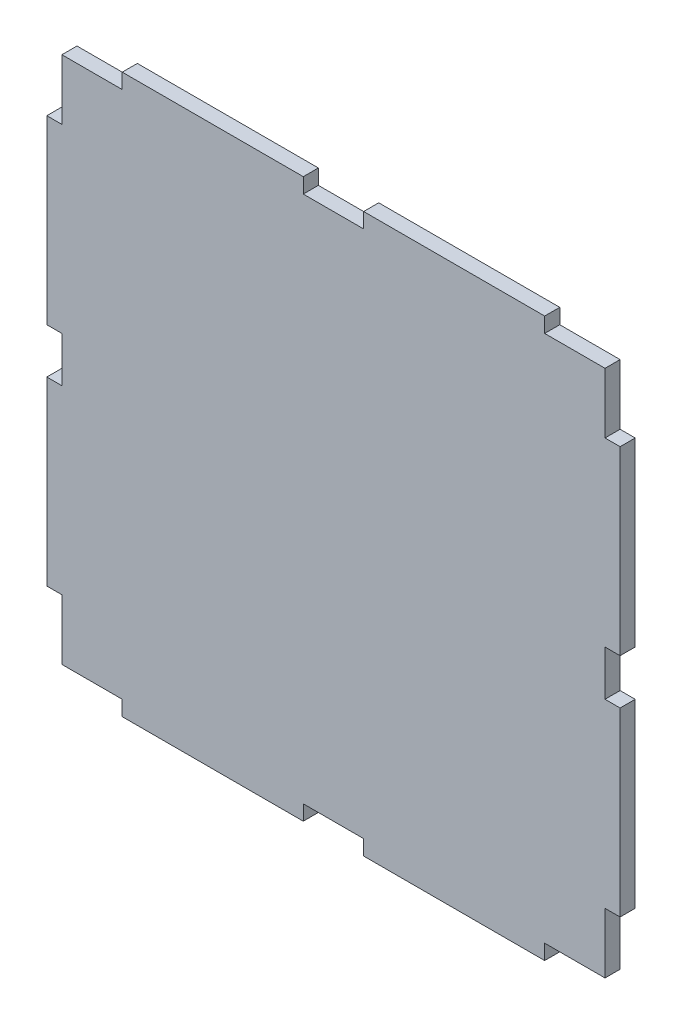
SolidWorks part; units mm, degrees
ref_plane "Front Plane" through (0, 0, 0) normal (0, 0, 1) x (1, 0, 0)
ref_plane "Top Plane" through (0, 0, 0) normal (0, 1, 0) x (1, 0, 0)
ref_plane "Right Plane" through (0, 0, 0) normal (1, 0, 0) x (0, 0, -1)
sketch "Sketch5" plane through (0, 0, 0) normal (0, 0, 1) x (1, 0, 0)
  line L0 (259.6128, -169.2784) -> (259.6128, -391.5284) construction
  line L1 (145.3128, -169.2784) -> (373.9128, -169.2784)
  line L2 (145.3128, -169.2784) -> (145.3128, -391.5284)
  line L3 (145.3128, -391.5284) -> (373.9128, -391.5284)
  line L4 (373.9128, -169.2784) -> (373.9128, -391.5284)
  line L5 (170.7128, -169.2784) -> (246.9128, -169.2784)
  line L6 (170.7128, -169.2784) -> (170.7128, -162.9284)
  line L7 (170.7128, -162.9284) -> (246.9128, -162.9284)
  line L8 (246.9128, -169.2784) -> (246.9128, -162.9284)
  line L9 (138.9628, -194.6784) -> (145.3128, -194.6784)
  line L10 (138.9628, -194.6784) -> (138.9628, -270.8784)
  line L11 (138.9628, -270.8784) -> (145.3128, -270.8784)
  line L12 (145.3128, -194.6784) -> (145.3128, -270.8784)
  line L13 (145.3128, -280.4034) -> (373.9128, -280.4034) construction
  line L14 (272.3128, -169.2784) -> (272.3128, -162.9284)
  line L15 (348.5128, -162.9284) -> (272.3128, -162.9284)
  line L16 (348.5128, -169.2784) -> (348.5128, -162.9284)
  line L17 (348.5128, -391.5284) -> (348.5128, -397.8784)
  line L18 (348.5128, -397.8784) -> (272.3128, -397.8784)
  line L19 (272.3128, -391.5284) -> (272.3128, -397.8784)
  line L20 (246.9128, -391.5284) -> (246.9128, -397.8784)
  line L21 (170.7128, -397.8784) -> (246.9128, -397.8784)
  line L22 (170.7128, -391.5284) -> (170.7128, -397.8784)
  line L23 (138.9628, -289.9284) -> (145.3128, -289.9284)
  line L24 (138.9628, -366.1284) -> (138.9628, -289.9284)
  line L25 (138.9628, -366.1284) -> (145.3128, -366.1284)
  line L26 (380.2628, -366.1284) -> (373.9128, -366.1284)
  line L27 (380.2628, -366.1284) -> (380.2628, -289.9284)
  line L28 (380.2628, -289.9284) -> (373.9128, -289.9284)
  line L29 (380.2628, -270.8784) -> (373.9128, -270.8784)
  line L30 (380.2628, -194.6784) -> (380.2628, -270.8784)
  line L31 (380.2628, -194.6784) -> (373.9128, -194.6784)
  dimension "D1" = 222.25
  dimension "D2" = 228.6
  dimension "D3" = 76.2
  dimension "D4" = 6.35
  dimension "D5" = 25.4
  dimension "D6" = 25.4
extrude "Boss-Extrude1" add sketch "Sketch5" along normal blind 6.35 contours L24 L25 L2 L23 | L3 L22 L21 L20 | L3 L19 L18 L17 | L27 L28 L4 L26 | L1 L16 L15 L14 | L30 L31 L4 L29 | L1 L8 L7 L6 | L10 L11 L2 L9
equation "\"width\"= 9in"
equation "\"Height\"= 18in"
equation "\"thick\"= 0.25"
equation "\"D1@Sketch5\"= \"width\" - \"thick\""
equation "\"D2@Sketch5\" = \"width\""
equation "\"D4@Sketch5\"=\"thick\""
equation "\"D1@Boss-Extrude1\"=\"thick\""
